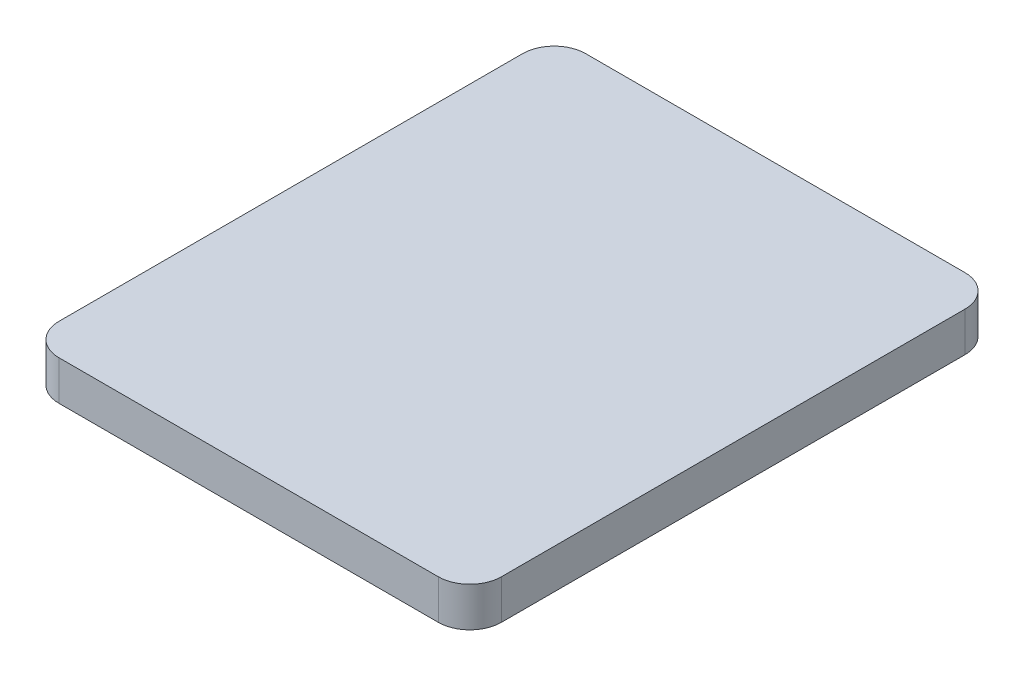
SolidWorks part; units mm, degrees
ref_plane "Front Plane" through (0, 0, 0) normal (0, 0, 1) x (1, 0, 0)
ref_plane "Top Plane" through (0, 0, 0) normal (0, 1, 0) x (1, 0, 0)
ref_plane "Right Plane" through (0, 0, 0) normal (1, 0, 0) x (0, 0, -1)
sketch "Sketch1" plane through (0, 0, 0) normal (0, 1, 0) x (1, 0, 0)
  line L0 (0, 0) -> (42, 0)
  line L1 (42, 0) -> (42, 50)
  line L4 (42, 50) -> (0, 50)
  line L7 (0, 50) -> (0, 0)
  dimension "D1" = 50
  dimension "D8" = 42
extrude "Boss-Extrude1" add sketch "Sketch1" along normal blind 3.75
fillet "Fillet1" radius 3 4 edges at (0, 1.875, -50) (42, 1.875, -50) (0, 1.875, 0) (42, 1.875, 0)
